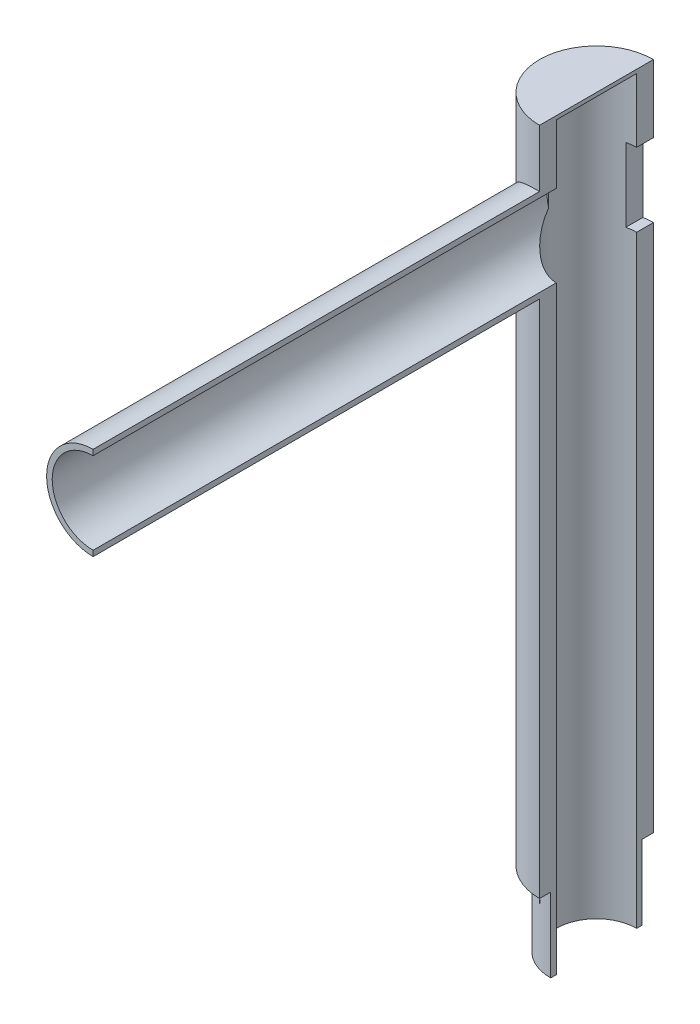
SolidWorks part; units mm, degrees
ref_plane "Front Plane" through (0, 0, 0) normal (0, 0, 1) x (1, 0, 0)
ref_plane "Top Plane" through (0, 0, 0) normal (0, 1, 0) x (1, 0, 0)
ref_plane "Right Plane" through (0, 0, 0) normal (1, 0, 0) x (0, 0, -1)
sketch "Sketch1" plane through (0, 0, 0) normal (0, 0, 1) x (1, 0, 0)
  line L0 (0, 259.8084) -> (0, 0) construction
  line L1 (0, 0) -> (-15.3, 0)
  line L2 (0, 0) -> (0, 180)
  line L3 (0, 180) -> (-15.3, 180)
  line L4 (-15.3, 0) -> (-15.3, 180)
  line L6 (-12.3, 0) -> (0, 0)
  line L7 (-12.3, 0) -> (-12.3, -20)
  line L8 (-12.3, -20) -> (0, -20)
  line L9 (0, 0) -> (0, -20)
  dimension "D1" = 12.3
  dimension "D2" = 180
  dimension "D3" = 20
  dimension "D4" = 3
revolve "Revolve1" add sketch "Sketch1" angle 360 about L0
ref_plane "Plane1" through (0, 0, 15.3) normal (0, 0, 1) x (1, 0, 0)
sketch "Sketch4" plane through (0, 0, 15.3) normal (0, 0, 1) x (1, 0, 0)
  circle A0 centre (0, 152.0713) radius 12.5
  dimension "D1" = 25
extrude "Boss-Extrude1" add sketch "Sketch4" along normal blind 120 and the other way blind 9
ref_plane "Plane2" through (-12.5, 0, 0) normal (-1, 0, 0) x (0, 0, 1)
sketch "Sketch6" plane through (-12.5, 0, 0) normal (-1, 0, 0) x (0, 0, 1)
  line L0 (135.3, 152.0713) -> (15.3, 152.0713) construction
  line L1 (97.3, 159.0713) -> (133.3, 159.0713)
  line L2 (97.3, 159.0713) -> (97.3, 145.0713)
  line L3 (97.3, 145.0713) -> (133.3, 145.0713)
  line L4 (133.3, 159.0713) -> (133.3, 145.0713)
  line L5 (135.3, 139.5713) -> (135.3, 164.5713) construction
  line L6 (15.3, -16.83) -> (15.3, 16.83) construction
  line L7 (95.3, 161.0713) -> (135.3, 161.0713)
  line L8 (135.3, 161.0713) -> (135.3, 143.0713)
  line L9 (95.3, 143.0713) -> (135.3, 143.0713)
  line L10 (95.3, 161.0713) -> (95.3, 143.0713)
  point P10 (133.3, 152.0713)
  point P16 (135.3, 152.0713)
  dimension "D1" = 36
  dimension "D2" = 14
  dimension "D3" = 2
extrude "Boss-Extrude2" add sketch "Sketch6" along normal blind 10 from offset 25 offset against normal yes
sketch "Sketch2" plane through (0, -20, 0) normal (0, -1, 0) x (1, 0, 0)
  circle A0 centre (0, 0) radius 10.8
  circle A1 centre (0, 0) radius 12.3 construction
  dimension "D1" = 1.5
extrude "Cut-Extrude1" cut sketch "Sketch2" against normal offset from surface (199 mm away) 1 up to face at (0, 180, 15.3)
sketch "Sketch5" plane through (0, 0, 135.3) normal (0, 0, 1) x (1, 0, 0)
  circle A0 centre (0, 152.0713) radius 11
  circle A1 centre (0, 152.0713) radius 12.5 construction
  dimension "D1" = 1.5
extrude "Cut-Extrude2" cut sketch "Sketch5" against normal blind 133
sketch "Sketch7" plane through (12.5, 0, 0) normal (1, 0, 0) x (0, 0, -1)
  line L1 (-133.3, 159.0713) -> (-97.3, 159.0713)
  line L2 (-133.3, 159.0713) -> (-133.3, 145.0713)
  line L3 (-133.3, 145.0713) -> (-97.3, 145.0713)
  line L4 (-97.3, 159.0713) -> (-97.3, 145.0713)
extrude "Cut-Extrude3" cut sketch "Sketch7" against normal blind 15
sketch "Sketch8" plane through (0, 0, 97.3) normal (0, 0, 1) x (1, 0, 0)
  line L0 (12.5, 159.0713) -> (12.5, 145.0713) construction
  line L1 (5.5, 163.0713) -> (0, 163.0713)
  line L2 (5.5, 163.0713) -> (5.5, 141.0713)
  line L3 (5.5, 141.0713) -> (0, 141.0713)
  line L4 (0, 163.0713) -> (0, 141.0713)
  arc A0 (5.5, 142.545) -> (5.5, 161.5975) centre (0, 152.0713) ccw
  point P4 (5.5, 152.0713)
  point P7 (12.5, 152.0713)
  arc M6 (8.4853, 159.0713) -> (8.4853, 145.0713) centre (0, 152.0713) cw
  dimension "D1" = 22
  dimension "D2" = 5.5
extrude "Boss-Extrude3" add sketch "Sketch8" against normal blind 6 from offset 11 contours L1 L4 L3 L2 | A0 L2 M6 offset against normal yes
sketch "Sketch9" plane through (0, 0, 0) normal (-1, 0, 0) x (0, 0, 1)
  line L0 (86.3, 152.0713) -> (80.3, 152.0713) construction
  line L1 (86.3, 163.0713) -> (86.3, 141.0713) construction
  line L2 (80.3, 163.0713) -> (80.3, 141.0713) construction
  circle A0 centre (83.05, 159.6713) radius 1.75
  circle A1 centre (83.05, 144.4713) radius 1.75
  dimension "D1" = 3.5
  dimension "D2" = 3.25
  dimension "D3" = 7.6
extrude "Boss-Extrude4" add sketch "Sketch9" along normal blind 2
sketch "Sketch10" plane through (12.5, 0, 0) normal (1, 0, 0) x (0, 0, -1)
  line L0 (-133.3, 152.0713) -> (-97.3, 152.0713) construction
  line L1 (-133.3, 159.0713) -> (-97.3, 159.0713)
  line L2 (-133.3, 159.0713) -> (-133.3, 145.0713)
  line L3 (-133.3, 145.0713) -> (-97.3, 145.0713)
  line L4 (-97.3, 159.0713) -> (-97.3, 145.0713)
  circle A0 centre (-127.3, 152.0713) radius 4
  circle A1 centre (-115.3, 152.0713) radius 4
  circle A2 centre (-103.3, 152.0713) radius 4
  dimension "D1" = 8
  dimension "D2" = 8
  dimension "D3" = 8
  dimension "D4" = 12
  dimension "D5" = 12
  dimension "D6" = 6
extrude "Boss-Extrude5" add sketch "Sketch10" against normal blind 1
sketch "Sketch11" plane through (12.5, 0, 0) normal (1, 0, 0) x (0, 0, -1)
  circle A0 centre (-127.3, 152.0713) radius 4
  circle A1 centre (-115.3, 152.0713) radius 4
  circle A2 centre (-103.3, 152.0713) radius 3.9534
sketch "Sketch12" plane through (0, 0, 135.3) normal (0, 0, 1) x (1, 0, 0)
  line L0 (-15.3, 180) -> (-15.3, 0) construction
  line L1 (-15.3, 180) -> (15.3, 180)
  line L2 (-15.3, 180) -> (-15.3, -20)
  line L3 (-15.3, -20) -> (15.3, -20)
  line L4 (15.3, 180) -> (15.3, -20)
  line L5 (15.3, 0) -> (15.3, 180) construction
  line L6 (15.3, 180) -> (-15.3, 180) construction
  line L7 (-12.3, -20) -> (12.3, -20) construction
  line L8 (0, 180) -> (0, 161.8066)
  line L9 (0, 142.0479) -> (0, -20)
  line L10 (0, 161.8066) -> (-2.6047, 161.8066)
  line L12 (0, 142.0479) -> (-2.6047, 142.0479)
  line L13 (-2.6047, 161.8066) -> (-2.6047, 142.0479)
  circle M5 centre (0, 152.0713) radius 11
  arc M6 (8.6747, 161.0713) -> (8.6747, 143.0713) centre (0, 152.0713) ccw
  line M7 (8.6747, 143.0713) -> (12.5, 143.0713)
  line M8 (12.5, 143.0713) -> (12.5, 161.0713)
  line M9 (12.5, 161.0713) -> (8.6747, 161.0713)
extrude "Cut-Extrude5" cut sketch "Sketch12" against normal blind 215 contours L9 L3 L4 L1 L8 M6 M9 M8 M7 | L9 L8 M5 M6 M7 M8 M9 | L10 L13 L12 L9 L8 M5
